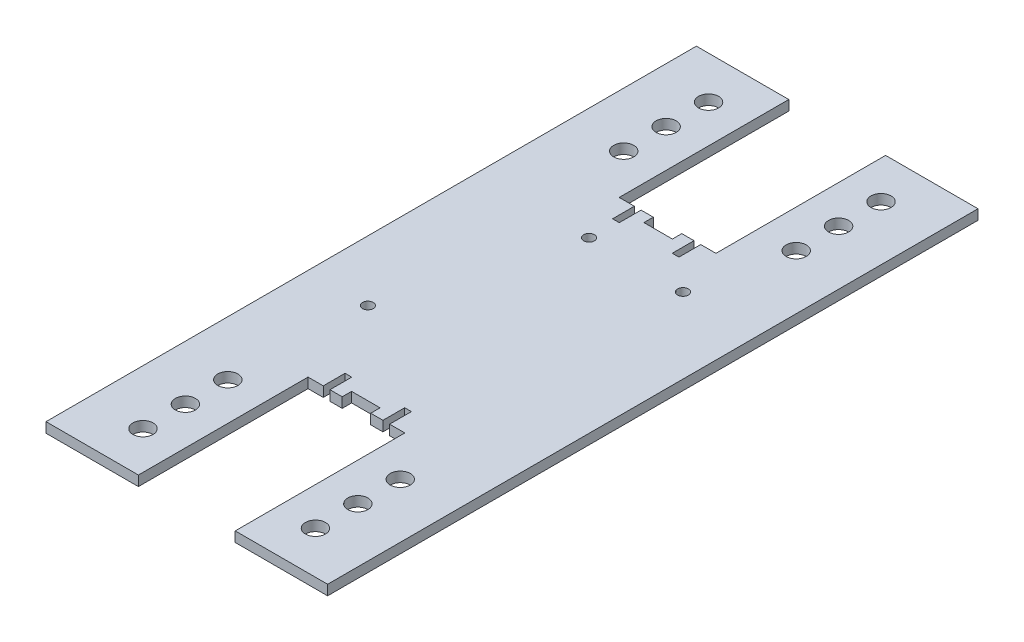
SolidWorks part; units mm, degrees
ref_plane "Plano frontal" through (0, 0, 0) normal (0, 0, 1) x (1, 0, 0)
ref_plane "Plano superior" through (0, 0, 0) normal (0, 1, 0) x (1, 0, 0)
ref_plane "Plano direito" through (0, 0, 0) normal (1, 0, 0) x (0, 0, -1)
sketch "Esboço1" plane through (0, 0, 0) normal (0, 0, 1) x (1, 0, 0)
  line L0 (-45.2293, 0) -> (38.7707, 0)
  line L1 (-45.2293, 0) -> (-45.2293, -3)
  line L2 (-45.2293, -3) -> (38.7707, -3)
  line L3 (38.7707, -3) -> (38.7707, 0)
  dimension "D1" = 84
  dimension "D2" = 3
extrude "Ressalto-extrusão1" add sketch "Esboço1" along normal blind 194
sketch "Esboço2" plane through (0, 0, 0) normal (0, 1, 0) x (1, 0, 0)
  line L0 (-3.2293, 0) -> (9.2707, 0)
  line L1 (38.7707, 0) -> (-45.2293, 0) construction
  line L2 (9.2707, 0) -> (9.2707, -50.6)
  line L3 (9.2707, -50.6) -> (-15.7293, -50.6)
  line L4 (-15.7293, -50.6) -> (-15.7293, 0)
  line L5 (-45.2293, 0) -> (38.7707, 0) construction
  line L6 (-15.7293, 0) -> (-3.2293, 0)
  line L7 (-3.2293, -194) -> (9.2707, -194)
  line L8 (38.7707, -194) -> (-45.2293, -194) construction
  line L9 (-3.2293, -194) -> (-15.7293, -194)
  line L10 (9.2707, -194) -> (9.2707, -143.4)
  line L11 (9.2707, -143.4) -> (-15.7293, -143.4)
  line L12 (-15.7293, -143.4) -> (-15.7293, -194)
  dimension "D1" = 12.5
  dimension "D2" = 12.5
  dimension "D3" = 50.6
  dimension "D4" = 12.5
  dimension "D5" = 12.5
  dimension "D6" = 50.6
extrude "Corte-extrusão1" cut sketch "Esboço2" against normal blind 194
sketch "Esboço7" plane through (0, 0, 0) normal (0, 1, 0) x (1, 0, 0)
  line L0 (-3.2293, -50.6) -> (14.2707, -50.6)
  line L1 (-15.7293, -50.6) -> (9.2707, -50.6) construction
  line L2 (14.2707, -50.6) -> (-20.7293, -50.6)
  line L3 (14.2707, -50.6) -> (14.2707, 0)
  line L4 (38.7707, 0) -> (9.2707, 0) construction
  line L5 (14.2707, 0) -> (-20.7293, 0)
  line L6 (-15.7293, 0) -> (-45.2293, 0) construction
  line L7 (-20.7293, 0) -> (-20.7293, -50.6)
  dimension "D1" = 17.5
  dimension "D2" = 17.5
extrude "Corte-extrusão5" cut sketch "Esboço7" against normal blind 10 contours L5 L7 L2 L0 L3
sketch "Esboço8" plane through (0, 0, 0) normal (0, 1, 0) x (1, 0, 0)
  line L0 (-3.2293, -143.4) -> (14.2707, -143.4)
  line L1 (9.2707, -143.4) -> (-15.7293, -143.4) construction
  line L2 (14.2707, -143.4) -> (-20.7293, -143.4)
  line L3 (-20.7293, -143.4) -> (-20.7293, -194)
  line L4 (-15.7293, -194) -> (-45.2293, -194) construction
  line L5 (-20.7293, -194) -> (14.2707, -194)
  line L6 (38.7707, -194) -> (9.2707, -194) construction
  line L7 (14.2707, -194) -> (14.2707, -143.4)
  dimension "D1" = 17.5
  dimension "D2" = 17.5
extrude "Corte-extrusão6" cut sketch "Esboço8" against normal blind 10 contours L5 L7 L0 L2 L3
sketch "Esboço9" plane through (0, 0, 0) normal (0, 1, 0) x (1, 0, 0)
  line L0 (11.2063, -50.6) -> (-17.6649, -50.6)
  line L1 (-20.7293, -50.6) -> (14.2707, -50.6) construction
  line L2 (11.2063, -50.6) -> (11.2063, 0)
  line L3 (11.2063, 0) -> (14.2707, 0)
  line L4 (14.2707, 0) -> (14.2707, -50.6)
  line L5 (14.2707, -50.6) -> (11.2063, -50.6)
  line L6 (-20.7293, -50.6) -> (-20.7293, 0)
  line L7 (-20.7293, 0) -> (-17.6649, 0)
  line L8 (-17.6649, 0) -> (-17.6649, -50.6)
  line L9 (-20.7293, -50.6) -> (-17.6649, -50.6)
  point P2 (-3.2293, -50.6)
  point P5 (-3.2293, -50.6)
  dimension "D1" = 28.8712
extrude "Ressalto-extrusão2" add sketch "Esboço9" against normal blind 3 contours L6 L9 L8 L7 | L5 L4 L3 L2
sketch "Esboço12" plane through (0, 0, 0) normal (0, 1, 0) x (1, 0, 0)
  line L0 (-3.2293, -50.6) -> (22.4918, -50.6)
  line L1 (-17.6649, -50.6) -> (11.2063, -50.6) construction
  line L2 (22.4918, -50.6) -> (22.4918, -37.95)
  line L3 (22.4918, -37.95) -> (22.4918, -25.3)
  line L4 (22.4918, -25.3) -> (22.4918, -12.65)
  line L5 (-3.2293, -50.6) -> (-28.9493, -50.6)
  line L6 (-28.9493, -50.6) -> (-28.9493, -12.65)
  line L7 (-28.9493, -12.65) -> (22.4918, -12.65)
  line L8 (-28.9493, -25.3) -> (-28.9493, -37.95)
  circle A0 centre (22.4918, -37.95) radius 3
  circle A1 centre (22.4918, -25.3) radius 3
  circle A2 centre (22.4918, -12.65) radius 3
  circle A3 centre (-28.9493, -12.65) radius 3
  circle A4 centre (-28.9493, -25.3) radius 3
  circle A5 centre (-28.9493, -37.95) radius 3
  dimension "D7" = 6
  dimension "D8" = 6
  dimension "D9" = 6
  dimension "D10" = 6
  dimension "D11" = 6
  dimension "D12" = 6
  dimension "D1" = 25.7211
  dimension "D2" = 12.65
  dimension "D3" = 12.65
  dimension "D4" = 12.65
  dimension "D5" = 25.72
  dimension "D6" = 12.65
sketch "Esboço13" plane through (0, 0, 0) normal (0, 0, 1) x (1, 0, 0)
  line L0 (-3.2293, -50.6) -> (22.4918, -50.6)
  dimension "D1" = 25.7211
extrude "Corte-extrusão8" cut sketch "Esboço12" against normal blind 3 contours A0 | A1 | A2 | A3 | A4 | A5
sketch "Esboço14" plane through (0, 0, 0) normal (0, 1, 0) x (1, 0, 0)
  line L0 (38.7707, -97) -> (-45.2293, -97)
  line L1 (38.7707, -194) -> (38.7707, 0) construction
  line L2 (-45.2293, -194) -> (-45.2293, 0) construction
  line L3 (-45.2293, -194) -> (-45.2293, 0)
  line L4 (-45.2293, 0) -> (-17.6649, 0)
  line L5 (-17.6649, 0) -> (-17.6649, -50.6)
  line L6 (-17.6649, -50.6) -> (11.2063, -50.6)
  line L7 (11.2063, -50.6) -> (11.2063, 0)
  line L8 (11.2063, 0) -> (38.7707, 0)
  line L9 (38.7707, 0) -> (38.7707, -194)
  line L10 (11.2063, -194) -> (38.7707, -194)
  line L11 (11.2063, -143.4) -> (11.2063, -194)
  line L12 (-17.6649, -143.4) -> (11.2063, -143.4)
  line L13 (-17.6649, -194) -> (-17.6649, -143.4)
  line L14 (-45.2293, -194) -> (-17.6649, -194)
  circle A0 centre (22.4918, -37.95) radius 3
  circle A1 centre (22.4918, -25.3) radius 3
  circle A2 centre (22.4918, -12.65) radius 3
  circle A3 centre (-28.9493, -12.65) radius 3
  circle A4 centre (-28.9493, -25.3) radius 3
  circle A5 centre (-28.9493, -37.95) radius 3
  circle A6 centre (-28.9493, -156.05) radius 3
  circle A7 centre (-28.9493, -168.7) radius 3
  circle A8 centre (-28.9493, -181.35) radius 3
  circle A9 centre (22.4918, -181.35) radius 3
  circle A10 centre (22.4918, -168.7) radius 3
  circle A11 centre (22.4918, -156.05) radius 3
extrude "Ressalto-extrusão3" add sketch "Esboço14" against normal blind 3 contours L3 L14 L13 L12 L11 L10 L9 L0 A10 A8 A6 A7 A9 A11
sketch "Esboço16" plane through (0, 0, 0) normal (0, 1, 0) x (1, 0, 0)
  line L0 (38.7707, -97) -> (-45.2293, -97) construction
  line L1 (38.7707, -194) -> (38.7707, 0) construction
  line L2 (-45.2293, -194) -> (-45.2293, 0) construction
  circle A0 centre (22.4918, -37.95) radius 3
  circle A1 centre (22.4918, -25.3) radius 3
  circle A2 centre (22.4918, -12.65) radius 3
  circle A3 centre (-28.9493, -12.65) radius 3
  circle A4 centre (-28.9493, -25.3) radius 3
  circle A5 centre (-28.9493, -37.95) radius 3
  circle A6 centre (-28.9493, -156.05) radius 3
  circle A7 centre (-28.9493, -168.7) radius 3
  circle A8 centre (-28.9493, -181.35) radius 3
  circle A9 centre (22.4918, -181.35) radius 3
  circle A10 centre (22.4918, -168.7) radius 3
  circle A11 centre (22.4918, -156.05) radius 3
extrude "Corte-extrusão9" cut sketch "Esboço16" against normal blind 3
sketch "Esboço17" plane through (0, 0, 0) normal (0, 1, 0) x (1, 0, 0)
  line L0 (-3.2293, -50.6) -> (-12.1293, -50.6)
  line L1 (-17.6649, -50.6) -> (11.2063, -50.6) construction
  line L2 (-3.2293, -50.6) -> (5.6707, -50.6)
  line L3 (5.6707, -50.6) -> (6.6707, -50.6)
  line L4 (6.6707, -50.6) -> (6.6707, -57.1)
  line L5 (6.6707, -57.1) -> (5.6707, -57.1)
  line L6 (5.6707, -57.1) -> (5.6707, -50.6)
  line L7 (5.6707, -57.1) -> (4.6707, -57.1)
  line L8 (4.6707, -57.1) -> (4.6707, -50.6)
  line L9 (4.6707, -50.6) -> (5.6707, -50.6)
  line L10 (-12.1293, -50.6) -> (-11.1293, -50.6)
  line L11 (-12.1293, -50.6) -> (-13.1293, -50.6)
  line L12 (-13.1293, -50.6) -> (-13.1293, -57.1)
  line L13 (-13.1293, -57.1) -> (-11.1293, -57.1)
  line L14 (-11.1293, -57.1) -> (-11.1293, -50.6)
  dimension "D1" = 8.9
  dimension "D2" = 8.9
  dimension "D3" = 1
  dimension "D4" = 1
  dimension "D5" = 6.5
  dimension "D6" = 6.5
  dimension "D7" = 2
  dimension "D8" = 1
extrude "Corte-extrusão10" cut sketch "Esboço17" against normal blind 10 contours L6 L5 L4 L3 | L8 L7 L6 L2 | L13 L14 L0 L11 L12
sketch "Esboço18" plane through (0, 0, 0) normal (0, 1, 0) x (1, 0, 0)
  line L0 (-3.2293, -50.6) -> (-3.2293, -97) construction
  line L1 (-11.1293, -50.6) -> (4.6707, -50.6) construction
  line L3 (6.6707, -143.4) -> (4.6707, -143.4)
  line L4 (-3.2293, -97) -> (-66.5235, -97) construction
  line L5 (-66.5235, -97) -> (64.7521, -97) construction
  line L6 (11.2063, -50.6) -> (6.6707, -50.6)
  line L7 (6.6707, -50.6) -> (6.6707, -57.1)
  line L8 (6.6707, -57.1) -> (4.6707, -57.1)
  line L9 (4.6707, -57.1) -> (4.6707, -50.6)
  line L10 (4.6707, -50.6) -> (-11.1293, -50.6)
  line L11 (-11.1293, -50.6) -> (-11.1293, -57.1)
  line L12 (-11.1293, -57.1) -> (-13.1293, -57.1)
  line L13 (-13.1293, -57.1) -> (-13.1293, -50.6)
  line L14 (-13.1293, -50.6) -> (-17.6649, -50.6)
  line L15 (-17.6649, -50.6) -> (11.2063, -50.6)
  line L16 (-11.1293, -143.4) -> (-13.1293, -143.4)
  line L17 (-11.1293, -136.9) -> (-13.1293, -136.9)
  line L18 (-13.1293, -136.9) -> (-13.1293, -143.4)
  line L19 (-11.1293, -143.4) -> (-11.1293, -136.9)
  line L22 (6.6707, -143.4) -> (6.6707, -136.9)
  line L23 (4.6707, -136.9) -> (4.6707, -143.4)
  line L24 (6.6707, -136.9) -> (4.6707, -136.9)
extrude "Corte-extrusão11" cut sketch "Esboço18" against normal blind 10 contours L22 L24 L23 L3 | L16 L19 L17 L18
sketch "Esboço19" plane through (0, 0, 0) normal (0, 1, 0) x (1, 0, 0)
  line L0 (-27.2293, -131) -> (-27.2293, -116)
  line L1 (-29.7293, -131) -> (23.2707, -131)
  line L2 (-29.7293, -131) -> (-29.7293, -63)
  line L3 (-29.7293, -63) -> (23.2707, -63)
  line L4 (23.2707, -131) -> (23.2707, -63)
  line L5 (-29.7293, -131) -> (-29.7293, -63)
  line L6 (16.2707, -131) -> (16.2707, -65.5)
  line L7 (38.7707, -194) -> (38.7707, 0) construction
  line L8 (-45.2293, -194) -> (-45.2293, 0)
  line L9 (-45.2293, 0) -> (-45.2293, -97)
  line L10 (-45.2293, -97) -> (38.7707, -97)
  line L11 (-29.7293, -131) -> (-29.7293, -63)
  line L12 (-29.7293, -97) -> (-29.7293, -63)
  line L13 (-29.7293, -97) -> (23.2707, -97)
  line L14 (23.2707, -97) -> (-3.2293, -97)
  line L15 (-3.2293, -97) -> (23.2707, -97)
  line L16 (-45.2293, -194) -> (38.7707, -194)
  line L17 (38.7707, -194) -> (-3.2293, -194)
  line L18 (-3.2293, -194) -> (-3.2293, 0)
  line L19 (-3.2293, -194) -> (-3.2293, 0)
  line L20 (-3.2293, -97) -> (-3.2293, 0)
  line L21 (-11.7293, -131) -> (-11.7293, -65.5)
  line L22 (16.2707, -65.5) -> (-11.7293, -65.5)
  circle A0 centre (-27.2293, -116) radius 1.6
  circle A1 centre (16.2707, -65.5) radius 1.6
  circle A2 centre (-11.7293, -65.5) radius 1.6
  dimension "D5" = 3.2
  dimension "D8" = 3.2
  dimension "D10" = 3.2
  dimension "D1" = 53
  dimension "D2" = 68
  dimension "D3" = 50.5
  dimension "D4" = 15
  dimension "D6" = 65.5
  dimension "D7" = 7
  dimension "D9" = 35
extrude "Corte-extrusão12" cut sketch "Esboço19" against normal blind 10
sketch "Esboço20" plane through (0, 0, 0) normal (0, 1, 0) x (1, 0, 0)
  line L1 (4.6707, -143.4) -> (-11.1293, -143.4) construction
  line L2 (-3.2293, -140.6) -> (1.0207, -140.6)
  line L3 (-3.2293, -140.6) -> (-7.4793, -140.6)
  line L4 (-7.4793, -140.6) -> (-7.4793, -143.4)
  line L5 (-7.4793, -143.4) -> (1.0207, -143.4)
  line L6 (1.0207, -143.4) -> (1.0207, -140.6)
  dimension "D2" = 4.25
  dimension "D3" = 4.25
extrude "Corte-extrusão13" cut sketch "Esboço20" against normal blind 10 contours L3 L4 L5 L6 L2
sketch "Esboço21" plane through (0, 0, 0) normal (0, 1, 0) x (1, 0, 0)
  line L1 (-11.1293, -50.6) -> (4.6707, -50.6) construction
  line L2 (-3.2293, -53.4) -> (-7.4793, -53.4)
  line L3 (-3.2293, -53.4) -> (1.0207, -53.4)
  line L4 (1.0207, -53.4) -> (1.0207, -50.6)
  line L5 (1.0207, -50.6) -> (-7.4793, -50.6)
  line L6 (-7.4793, -50.6) -> (-7.4793, -53.4)
  dimension "D2" = 4.25
  dimension "D3" = 4.25
extrude "Corte-extrusão14" cut sketch "Esboço21" against normal blind 10 contours L3 L4 L5 L6 L2
